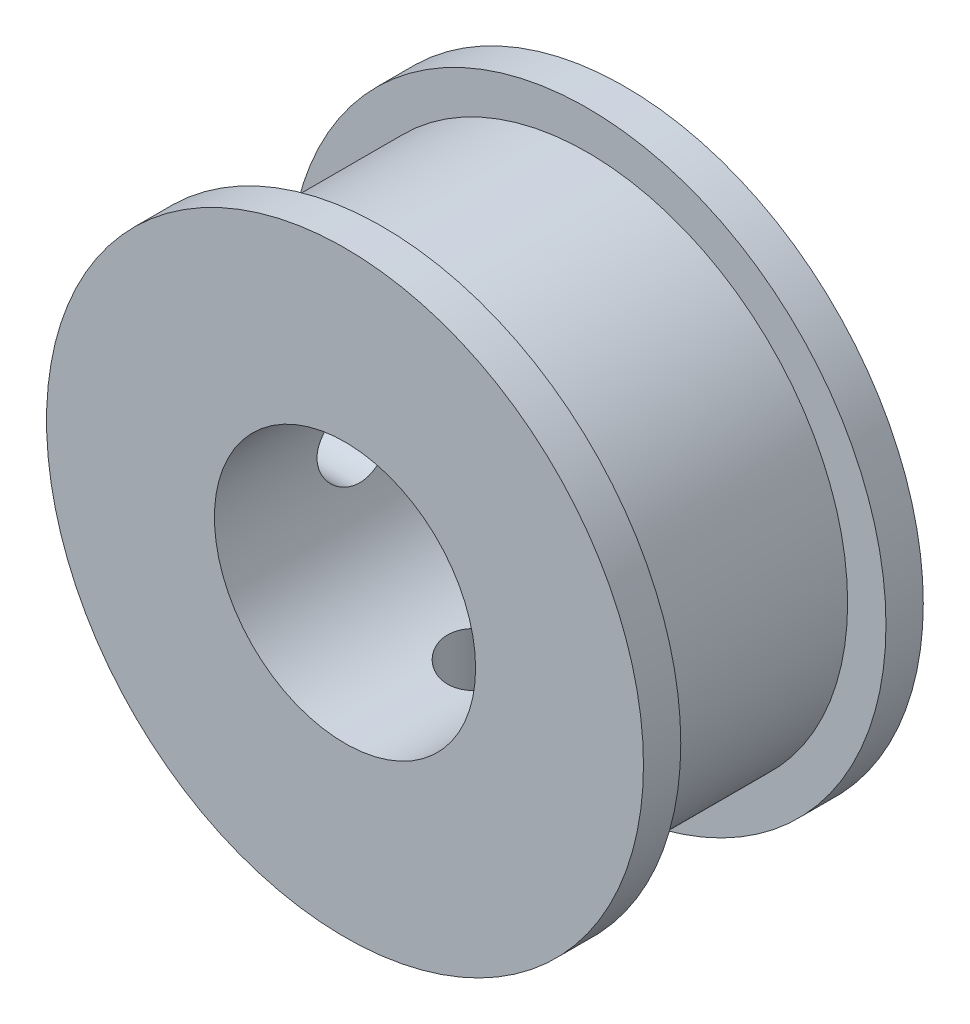
SolidWorks part; units mm, degrees
ref_plane "前视基准面" through (0, 0, 0) normal (0, 0, 1) x (1, 0, 0)
ref_plane "上视基准面" through (0, 0, 0) normal (0, 1, 0) x (1, 0, 0)
ref_plane "右视基准面" through (0, 0, 0) normal (1, 0, 0) x (0, 0, -1)
sketch "草图1" plane through (0, 0, 0) normal (0, 0, 1) x (1, 0, 0)
  circle A0 centre (0, 0) radius 16
  dimension "D1" = 32
extrude "凸台-拉伸1" add sketch "草图1" along normal blind 2 contours A0
sketch "草图2" plane through (0, 0, 2) normal (0, 0, 1) x (1, 0, 0)
  circle A0 centre (0, 0) radius 13.945
  dimension "D1" = 27.89
extrude "凸台-拉伸2" add sketch "草图2" along normal blind 11
sketch "草图3" plane through (0, 0, 13) normal (0, 0, 1) x (1, 0, 0)
  circle A0 centre (0, 0) radius 16
  dimension "D1" = 32
extrude "凸台-拉伸3" add sketch "草图3" along normal blind 2
sketch "草图4" plane through (0, 0, 15) normal (0, 0, 1) x (1, 0, 0)
  circle A0 centre (0, 0) radius 7
  dimension "D1" = 14
extrude "切除-拉伸1" cut sketch "草图4" against normal blind 15
sketch "草图5" plane through (0, 0, 0) normal (0, 1, 0) x (1, 0, 0)
  line L0 (0, 0) -> (0, -15) construction
  line L1 (-16, -15) -> (16, -15) construction
  circle A0 centre (0, -7.5) radius 2
extrude "切除-拉伸2" cut sketch "草图5" against normal blind 20
sketch "草图8" plane through (0, 0, 0) normal (1, 0, 0) x (0, 0, -1)
  line L0 (-15, 0) -> (0, 0) construction
  line L1 (-15, 16) -> (-15, -16) construction
  circle A0 centre (-7.5, 0) radius 2
extrude "切除-拉伸3" cut sketch "草图8" against normal blind 20
